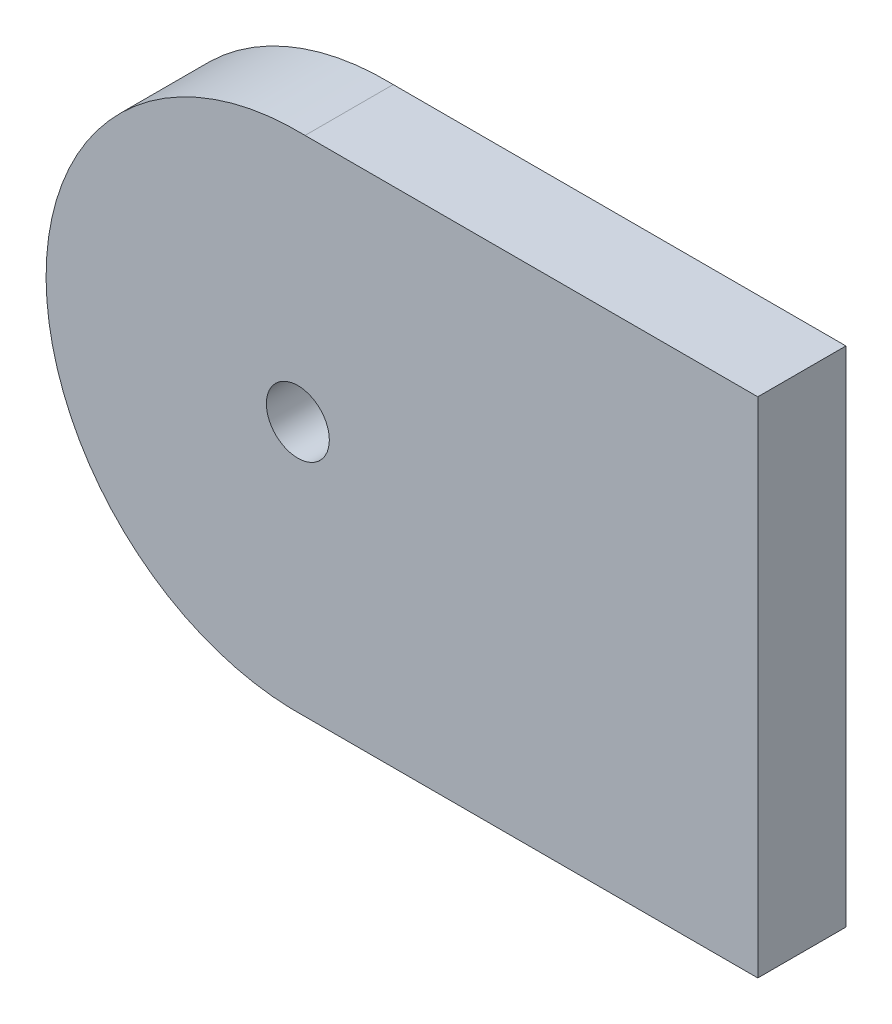
SolidWorks part; units mm, degrees
ref_plane "Front" through (0, 0, 0) normal (0, 0, 1) x (1, 0, 0)
ref_plane "Top" through (0, 0, 0) normal (0, 1, 0) x (1, 0, 0)
ref_plane "Right" through (0, 0, 0) normal (1, 0, 0) x (0, 0, -1)
sketch "Sketch1" plane through (0, 0, 0) normal (0, 0, 1) x (1, 0, 0)
  line L0 (1.4586, 50.7791) -> (16.6033, 50.7791)
  line L1 (16.6033, 50.7791) -> (16.6033, -50.7791)
  line L2 (16.6033, -50.7791) -> (-1.4586, -50.7791)
  circle A0 centre (0, 0) radius 6.35
  arc A1 (1.4586, 50.7791) -> (-1.4586, -50.7791) centre (0, 0) ccw
  dimension "D1" = 12.7
  dimension "D2" = 50.8
extrude "Boss-Extrude1" add sketch "Sketch1" along normal blind 8.89 and the other way blind 8.89
sketch "Sketch2" plane through (16.6033, 0, 0) normal (1, 0, 0) x (0, 0, -1)
  line L5 (-8.89, -50.7791) -> (8.89, -50.7791)
  line L6 (-8.89, -50.7791) -> (-8.89, 50.7791)
  line L7 (-8.89, 50.7791) -> (8.89, 50.7791)
  line L8 (8.89, -50.7791) -> (8.89, 50.7791)
  point P0 (0, 0)
  point P1 (0, 0)
extrude "Boss-Extrude2" add sketch "Sketch2" along normal blind 76.2
